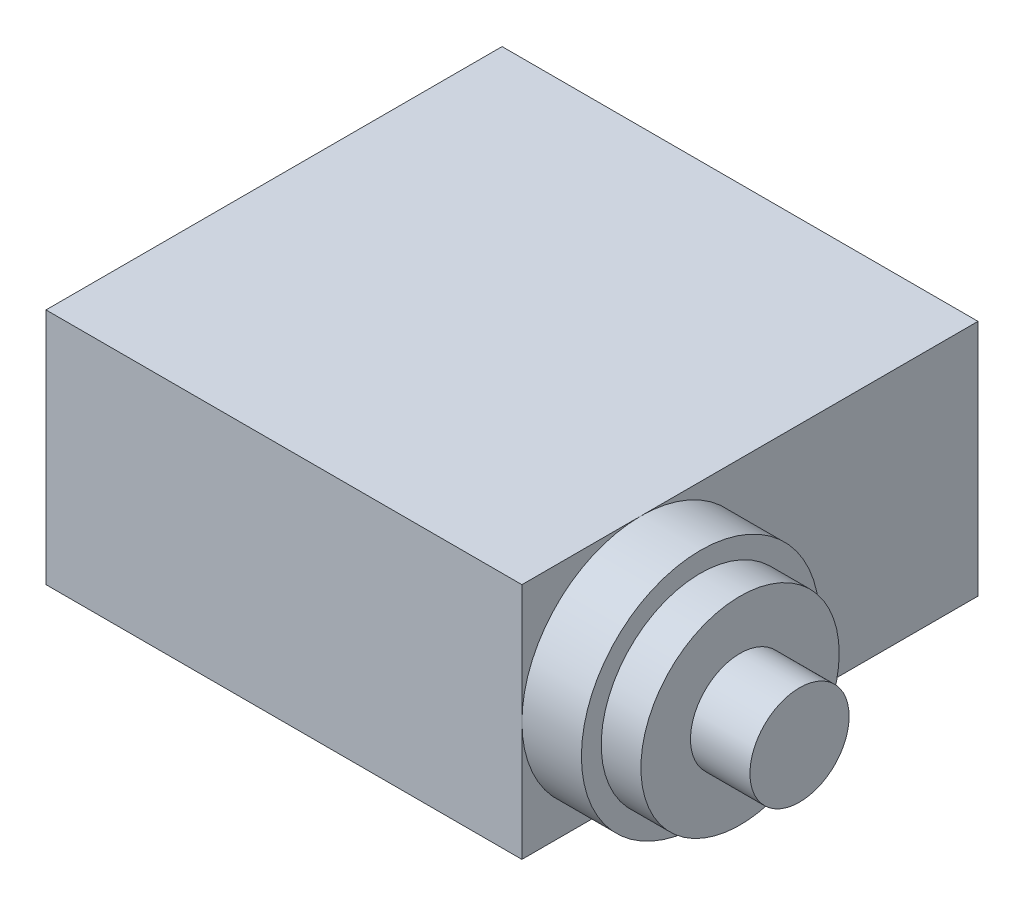
SolidWorks part; units mm, degrees
material "Manual Density from Real Component Servomotore"
ref_plane "Piano frontale" through (0, 0, 0) normal (0, 0, 1) x (1, 0, 0)
ref_plane "Piano superiore" through (0, 0, 0) normal (0, 1, 0) x (1, 0, 0)
ref_plane "Piano destro" through (0, 0, 0) normal (1, 0, 0) x (0, 0, -1)
sketch "Schizzo1" plane through (0, 0, 0) normal (0, 1, 0) x (1, 0, 0)
  line L1 (12, -11.5) -> (-12, -11.5)
  line L2 (12, -11.5) -> (12, 11.5)
  line L3 (12, 11.5) -> (-12, 11.5)
  line L4 (-12, -11.5) -> (-12, 11.5)
  line L5 (12, -11.5) -> (-12, 11.5) construction
  line L6 (12, 11.5) -> (-12, -11.5) construction
  point P0 (0, 0)
  dimension "D1" = 23
  dimension "D2" = 24
extrude "CorpoCentrale" add sketch "Schizzo1" along normal blind 12
sketch "Schizzo2" plane through (12, 0, 0) normal (1, 0, 0) x (0, 0, -1)
  line L0 (-11.5, 12) -> (11.5, 12) construction
  line L1 (-11.5, 12) -> (-11.5, 0) construction
  line L2 (-11.5, 0) -> (11.5, 0) construction
  circle A0 centre (-5.5, 6) radius 6
extrude "Estrusione-Estrusione2" add sketch "Schizzo2" along normal blind 3
sketch "Schizzo3" plane through (15, 0, 0) normal (1, 0, 0) x (0, 0, -1)
  circle A0 centre (-5.5, 6) radius 5
  arc A1 (-5.5, 0) -> (-5.5, 12) centre (-5.5, 6) ccw construction
  dimension "D1" = 10
extrude "Estrusione-Estrusione3" add sketch "Schizzo3" along normal blind 2
sketch "Schizzo4" plane through (17, 0, 0) normal (1, 0, 0) x (0, 0, -1)
  circle A0 centre (-5.5, 6) radius 2.5
  dimension "D1" = 5
extrude "Estrusione-Estrusione4" add sketch "Schizzo4" along normal blind 3
